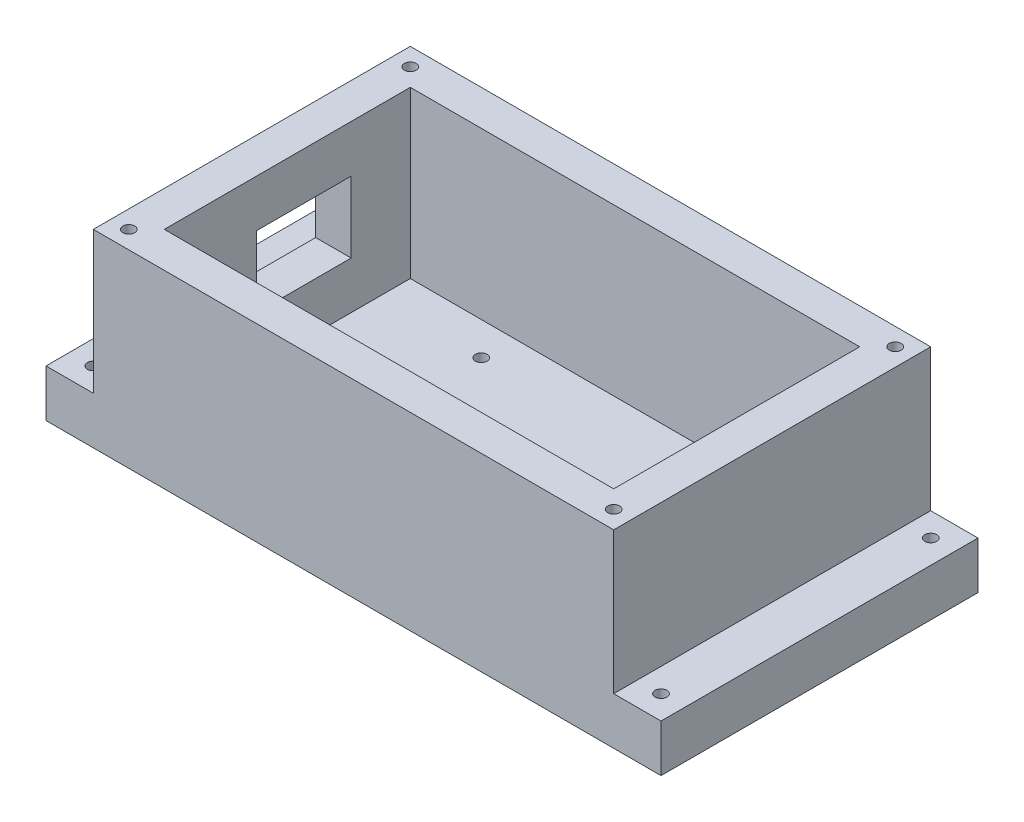
SolidWorks part; units mm, degrees
material "ABS"
ref_plane "Front Plane" through (0, 0, 0) normal (0, 0, 1) x (1, 0, 0)
ref_plane "Top Plane" through (0, 0, 0) normal (0, 1, 0) x (1, 0, 0)
ref_plane "Right Plane" through (0, 0, 0) normal (1, 0, 0) x (0, 0, -1)
sketch "Sketch1" plane through (0, 0, 0) normal (0, 1, 0) x (1, 0, 0)
  line L9 (-34.925, 69.215) -> (130.175, 69.215)
  line L10 (-34.925, 69.215) -> (-34.925, -15.875)
  line L11 (-34.925, -15.875) -> (130.175, -15.875)
  line L12 (130.175, 69.215) -> (130.175, -15.875)
  dimension "D2" = 15.875
  dimension "D3" = 34.925
  dimension "D4" = 85.09
  dimension "D5" = 165.1
extrude "Boss-Extrude2" add sketch "Sketch1" along normal blind 12.7 contours L10 L11 L12 L9
sketch "Sketch3" plane through (0, 12.7, 0) normal (0, 1, 0) x (1, 0, 0)
  line L0 (-34.925, 69.215) -> (-34.925, -15.875) construction
  line L1 (-22.225, 69.215) -> (117.475, 69.215)
  line L2 (-22.225, 69.215) -> (-22.225, -15.875)
  line L3 (-22.225, -15.875) -> (117.475, -15.875)
  line L4 (117.475, 69.215) -> (117.475, -15.875)
  line L6 (130.175, 69.215) -> (130.175, -15.875) construction
  line L8 (-34.925, 69.215) -> (130.175, 69.215) construction
  dimension "D1" = 12.7
  dimension "D3" = 12.7
extrude "Boss-Extrude3" add sketch "Sketch3" along normal blind 38.1
sketch "Sketch4" plane through (0, 50.8, 0) normal (0, 1, 0) x (1, 0, 0)
  line L0 (-22.225, 69.215) -> (-22.225, -15.875) construction
  line L1 (-12.7, 59.69) -> (107.95, 59.69)
  line L2 (-12.7, 59.69) -> (-12.7, -6.35)
  line L3 (-12.7, -6.35) -> (107.95, -6.35)
  line L4 (107.95, 59.69) -> (107.95, -6.35)
  line L5 (117.475, -15.875) -> (117.475, 69.215) construction
  line L6 (117.475, 69.215) -> (-22.225, 69.215) construction
  line L7 (-22.225, -15.875) -> (117.475, -15.875) construction
  dimension "D1" = 9.525
  dimension "D2" = 9.525
  dimension "D3" = 9.525
  dimension "D4" = 9.525
extrude "Cut-Extrude1" cut sketch "Sketch4" against normal blind 44.45
sketch "Sketch5" plane through (0, 6.35, 0) normal (0, 1, 0) x (1, 0, 0)
  circle A0 centre (15.24, 50.8) radius 1.5875
  circle A1 centre (13.97, 2.54) radius 1.5875
  circle A2 centre (90.17, 50.8) radius 1.5875
  circle A3 centre (96.52, 2.54) radius 1.5875
  dimension "D1" = 3.175
  dimension "D2" = 3.175
  dimension "D3" = 3.175
  dimension "D4" = 3.175
  dimension "D5" = 2.54
  dimension "D6" = 13.97
  dimension "D7" = 96.52
  dimension "D8" = 50.8
  dimension "D9" = 15.24
  dimension "D10" = 90.17
sketch "Sketch8" plane through (0, 50.8, 0) normal (0, 1, 0) x (1, 0, 0)
  line L0 (117.475, 69.215) -> (-22.225, 69.215) construction
  line L1 (-22.225, 69.215) -> (-22.225, -15.875) construction
  line L3 (117.475, -15.875) -> (117.475, 69.215) construction
  line L4 (-22.225, -15.875) -> (117.475, -15.875) construction
  circle A0 centre (-17.4625, 64.4525) radius 1.5875
  circle A1 centre (-17.4625, -11.1125) radius 1.5875
  circle A2 centre (112.7125, -11.1125) radius 1.5875
  circle A3 centre (112.7125, 64.4525) radius 1.5875
  dimension "D5" = 3.175
  dimension "D6" = 3.175
  dimension "D7" = 3.175
  dimension "D8" = 3.175
  dimension "D1" = 4.7625
  dimension "D2" = 4.7625
  dimension "D3" = 4.7625
  dimension "D4" = 4.7625
extrude "Cut-Extrude3" cut sketch "Sketch5" against normal through all
extrude "Cut-Extrude4" cut sketch "Sketch8" against normal blind 25.4
sketch "Sketch11" plane through (0, 12.7, 0) normal (0, 1, 0) x (1, 0, 0)
  line L3 (-34.925, 69.215) -> (-22.225, 69.215) construction
  line L5 (-34.925, 69.215) -> (-34.925, -15.875) construction
  line L6 (-34.925, -15.875) -> (-22.225, -15.875) construction
  line L7 (130.175, 69.215) -> (130.175, -15.875) construction
  circle A0 centre (-28.575, 62.865) radius 1.5875
  circle A1 centre (-28.575, -9.525) radius 1.5875
  circle A2 centre (123.825, -9.525) radius 1.5875
  circle A3 centre (123.825, 62.865) radius 1.5875
  dimension "D5" = 3.175
  dimension "D6" = 3.175
  dimension "D7" = 3.175
  dimension "D8" = 3.175
  dimension "D1" = 6.35
  dimension "D2" = 6.35
  dimension "D3" = 6.35
  dimension "D4" = 6.35
extrude "Cut-Extrude6" cut sketch "Sketch11" against normal through all
sketch "Sketch14" plane through (0, 0, 0) normal (0, -1, 0) x (1, 0, 0)
  line L1 (17.057, -1.7978) -> (14.8708, 0.5045)
  line L2 (14.8708, 0.5045) -> (11.7837, -0.2376)
  line L3 (11.7837, -0.2376) -> (10.883, -3.2822)
  line L4 (10.883, -3.2822) -> (13.0692, -5.5845)
  line L5 (13.0692, -5.5845) -> (16.1563, -4.8424)
  line L6 (16.1563, -4.8424) -> (17.057, -1.7978)
  line L7 (18.415, -50.8) -> (16.8275, -48.0504)
  line L8 (16.8275, -48.0504) -> (13.6525, -48.0504)
  line L9 (13.6525, -48.0504) -> (12.065, -50.8)
  line L10 (12.065, -50.8) -> (13.6525, -53.5496)
  line L11 (13.6525, -53.5496) -> (16.8275, -53.5496)
  line L12 (16.8275, -53.5496) -> (18.415, -50.8)
  line L13 (93.009, -52.2215) -> (92.8206, -49.0521)
  line L14 (92.8206, -49.0521) -> (89.9815, -47.6306)
  line L15 (89.9815, -47.6306) -> (87.331, -49.3785)
  line L16 (87.331, -49.3785) -> (87.5194, -52.5479)
  line L17 (87.5194, -52.5479) -> (90.3585, -53.9694)
  line L18 (90.3585, -53.9694) -> (93.009, -52.2215)
  line L19 (99.581, -3.383) -> (98.7806, -0.3106)
  line L20 (98.7806, -0.3106) -> (95.7196, 0.5324)
  line L21 (95.7196, 0.5324) -> (93.459, -1.697)
  line L22 (93.459, -1.697) -> (94.2594, -4.7694)
  line L23 (94.2594, -4.7694) -> (97.3204, -5.6124)
  line L24 (97.3204, -5.6124) -> (99.581, -3.383)
  circle A0 centre (13.97, -2.54) radius 2.7496 construction
  circle A1 centre (15.24, -50.8) radius 2.7496 construction
  circle A2 centre (90.17, -50.8) radius 2.7496 construction
  circle A3 centre (96.52, -2.54) radius 2.7496 construction
  dimension "D1" = 3.175
  dimension "D2" = 3.175
  dimension "D3" = 3.175
  dimension "D4" = 3.175
extrude "Cut-Extrude7" cut sketch "Sketch14" against normal blind 3.175
sketch "Sketch15" plane through (-22.225, 0, 0) normal (-1, 0, 0) x (0, 0, 1)
  line L1 (-43.815, 38.1) -> (-18.415, 38.1)
  line L2 (-43.815, 38.1) -> (-43.815, 19.05)
  line L3 (-43.815, 19.05) -> (-18.415, 19.05)
  line L4 (-18.415, 38.1) -> (-18.415, 19.05)
  line L5 (-69.215, 50.8) -> (15.875, 50.8) construction
  line L6 (-69.215, 50.8) -> (-69.215, 12.7) construction
  dimension "D1" = 12.7
  dimension "D2" = 25.4
  dimension "D3" = 25.4
  dimension "D4" = 19.05
extrude "Cut-Extrude8" cut sketch "Sketch15" against normal up to next
